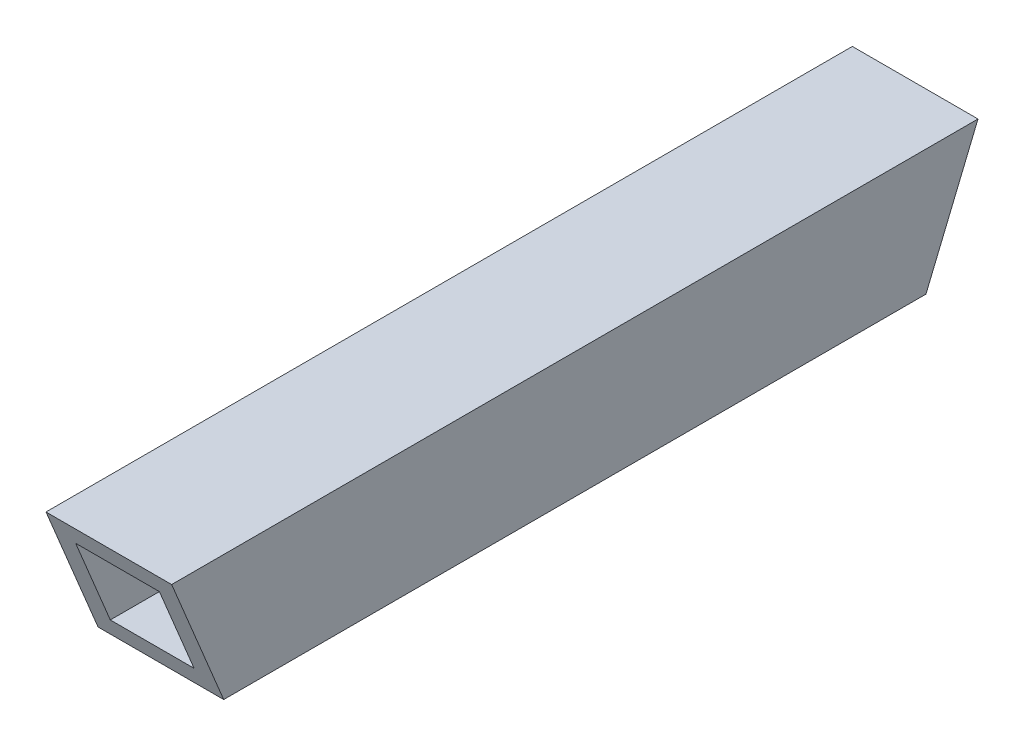
SolidWorks part; units mm, degrees
material "6061-T6 (SS)"
ref_plane "Front Plane" through (0, 0, 0) normal (0, 0, 1) x (1, 0, 0)
ref_plane "Top Plane" through (0, 0, 0) normal (0, 1, 0) x (1, 0, 0)
ref_plane "Right Plane" through (0, 0, 0) normal (1, 0, 0) x (0, 0, -1)
sketch "Sketch1" plane through (0, 0, 0) normal (0, 0, 1) x (1, 0, 0)
  line L1 (-9.525, -9.525) -> (9.525, -9.525)
  line L2 (-9.525, -9.525) -> (-9.525, 9.525)
  line L3 (-9.525, 9.525) -> (9.525, 9.525)
  line L4 (9.525, -9.525) -> (9.525, 9.525)
  line L5 (-9.525, -9.525) -> (9.525, 9.525) construction
  line L6 (-9.525, 9.525) -> (9.525, -9.525) construction
  line L7 (-6.35, -6.35) -> (6.35, -6.35)
  line L8 (-6.35, -6.35) -> (-6.35, 6.35)
  line L9 (-6.35, 6.35) -> (6.35, 6.35)
  line L10 (6.35, -6.35) -> (6.35, 6.35)
  line L11 (-6.35, -6.35) -> (6.35, 6.35) construction
  line L12 (-6.35, 6.35) -> (6.35, -6.35) construction
  point P0 (0, 0)
  point P5 (0, 0)
  dimension "D1" = 19.05
  dimension "D2" = 3.175
extrude "Boss-Extrude1" add sketch "Sketch1" along normal mid plane 122.2375
sketch "Sketch2" plane through (9.525, 0, 0) normal (1, 0, 0) x (0, 0, -1)
  line L0 (-61.1187, 9.525) -> (-53.228, -9.525)
  line L1 (-61.1187, -9.525) -> (61.1187, -9.525) construction
  line L2 (-53.228, -9.525) -> (-61.1187, -9.525)
  line L3 (-61.1187, -9.525) -> (-61.1187, 9.525)
  line L4 (61.1187, 9.525) -> (53.228, -9.525)
  line L5 (53.228, -9.525) -> (61.1187, -9.525)
  line L6 (61.1187, -9.525) -> (61.1187, 9.525)
  dimension "D1" = 22.5
  dimension "D2" = 22.5
extrude "Cut-Extrude1" cut sketch "Sketch2" against normal through all
